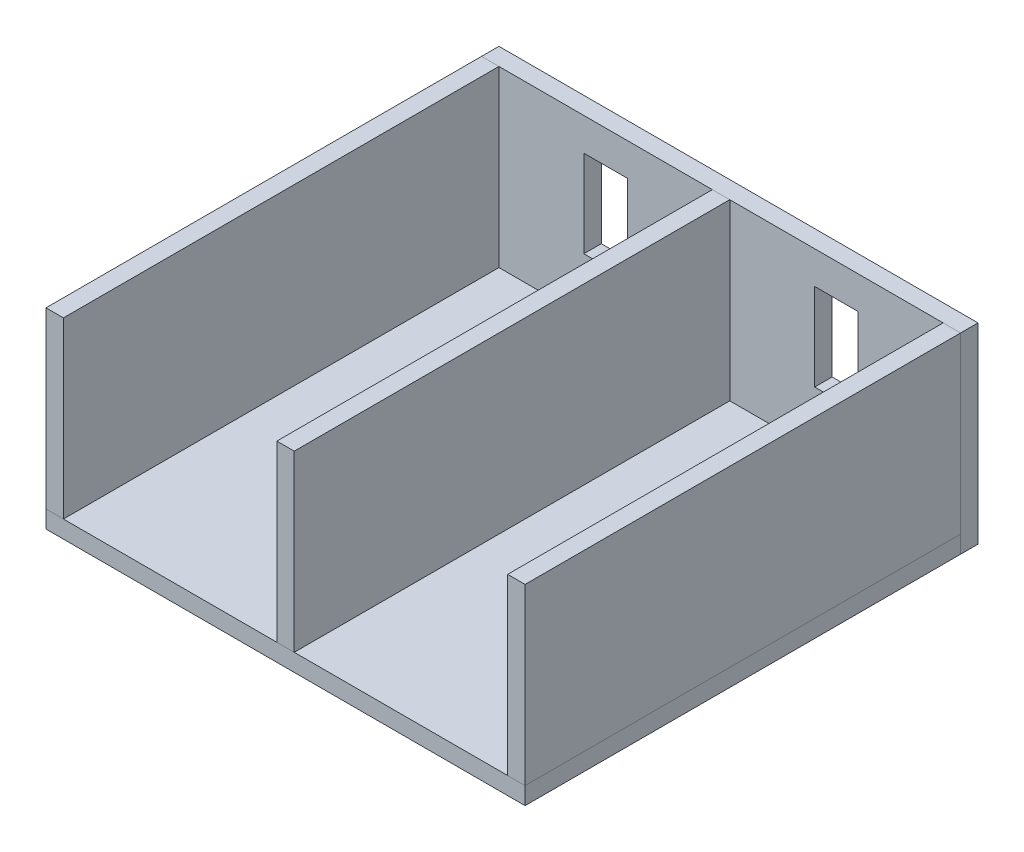
SolidWorks part; units mm, degrees
ref_plane "Front Plane" through (0, 0, 0) normal (0, 0, 1) x (1, 0, 0)
ref_plane "Top Plane" through (0, 0, 0) normal (0, 1, 0) x (1, 0, 0)
ref_plane "Right Plane" through (0, 0, 0) normal (1, 0, 0) x (0, 0, -1)
sketch "Sketch1" plane through (0, 0, 0) normal (0, 1, 0) x (1, 0, 0)
  line L1 (-110, -100) -> (110, -100)
  line L2 (-110, -100) -> (-110, 100)
  line L3 (-110, 100) -> (110, 100)
  line L4 (110, -100) -> (110, 100)
  line L5 (-110, -100) -> (110, 100) construction
  line L6 (-110, 100) -> (110, -100) construction
  point P0 (0, 0)
  dimension "D1" = 220
  dimension "D2" = 200
extrude "Boss-Extrude1" add sketch "Sketch1" along normal blind 8
sketch "Sketch2" plane through (0, 8, 0) normal (0, 1, 0) x (1, 0, 0)
  line L0 (110, 100) -> (-110, 100) construction
  line L1 (-110, -100) -> (-102, -100)
  line L2 (-110, -100) -> (-110, 100)
  line L3 (-110, 100) -> (-102, 100)
  line L4 (-102, -100) -> (-102, 100)
  line L6 (110, -100) -> (102, -100)
  line L7 (110, -100) -> (110, 100)
  line L8 (110, 100) -> (102, 100)
  line L9 (102, -100) -> (102, 100)
  line L10 (-4, -100) -> (4, -100)
  line L11 (-4, -100) -> (-4, 100)
  line L12 (-4, 100) -> (4, 100)
  line L13 (4, -100) -> (4, 100)
  line L14 (-4, -100) -> (4, 100) construction
  line L15 (-4, 100) -> (4, -100) construction
  point P12 (0, 0)
  dimension "D1" = 8
  dimension "D2" = 8
  dimension "D3" = 8
extrude "Boss-Extrude2" add sketch "Sketch2" along normal blind 80 separate body
sketch "Sketch3" plane through (0, 0, -100) normal (0, 0, -1) x (-1, 0, 0)
  line L1 (-110, 88) -> (110, 88)
  line L2 (-110, 88) -> (-110, 0)
  line L3 (-110, 0) -> (110, 0)
  line L4 (110, 88) -> (110, 0)
extrude "Boss-Extrude3" add sketch "Sketch3" along normal blind 8 separate body
sketch "Sketch4" plane through (0, 0, -108) normal (0, 0, -1) x (-1, 0, 0)
  line L0 (110, 8) -> (-110, 8) construction
  line L1 (63, 33) -> (43, 33)
  line L2 (63, 33) -> (63, 73)
  line L3 (63, 73) -> (43, 73)
  line L4 (43, 33) -> (43, 73)
  line L5 (63, 33) -> (43, 73) construction
  line L6 (63, 73) -> (43, 33) construction
  line L7 (-43, 33) -> (-63, 33)
  line L8 (-43, 33) -> (-43, 73)
  line L9 (-43, 73) -> (-63, 73)
  line L10 (-63, 33) -> (-63, 73)
  line L11 (-43, 33) -> (-63, 73) construction
  line L12 (-43, 73) -> (-63, 33) construction
  line L13 (-4, 88) -> (-4, 8) construction
  point P0 (53, 53)
  point P5 (-53, 53)
  dimension "D1" = 20
  dimension "D2" = 40
  dimension "D3" = 49
  dimension "D4" = 45
  dimension "D5" = 20
  dimension "D6" = 40
  dimension "D7" = 49
  dimension "D8" = 45
extrude "Cut-Extrude1" cut sketch "Sketch4" against normal through all
